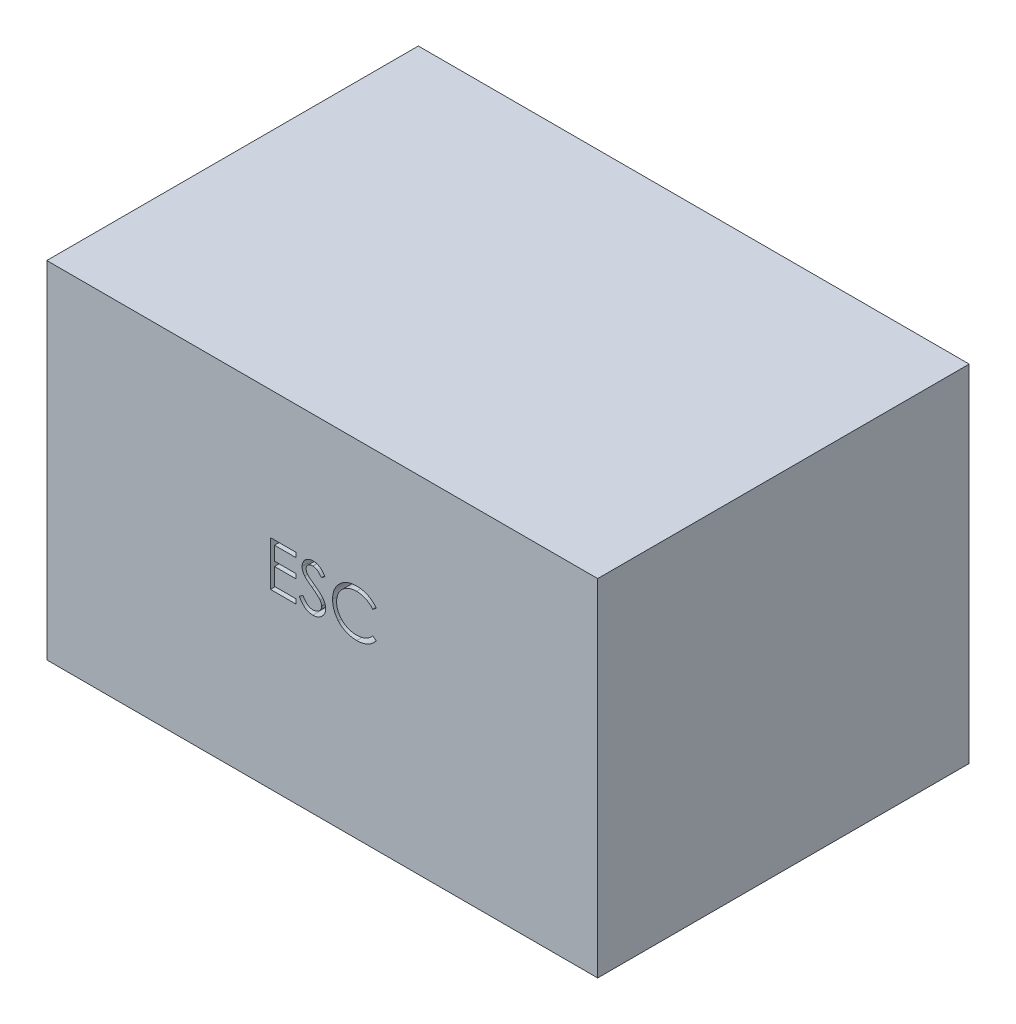
SolidWorks part; units mm, degrees
ref_plane "Front Plane" through (0, 0, 0) normal (0, 0, 1) x (1, 0, 0)
ref_plane "Top Plane" through (0, 0, 0) normal (0, 1, 0) x (1, 0, 0)
ref_plane "Right Plane" through (0, 0, 0) normal (1, 0, 0) x (0, 0, -1)
sketch "Sketch1" plane through (0, 0, 0) normal (0, 1, 0) x (1, 0, 0)
  line L1 (-21.5, -14.5) -> (21.5, -14.5)
  line L2 (-21.5, -14.5) -> (-21.5, 14.5)
  line L3 (-21.5, 14.5) -> (21.5, 14.5)
  line L4 (21.5, -14.5) -> (21.5, 14.5)
  line L5 (-21.5, -14.5) -> (21.5, 14.5) construction
  line L6 (-21.5, 14.5) -> (21.5, -14.5) construction
  point P0 (0, 0)
  dimension "D1" = 43
  dimension "D2" = 29
extrude "Boss-Extrude1" add sketch "Sketch1" along normal blind 27
sketch "Sketch2" plane through (0, 0, 14.5) normal (0, 0, 1) x (1, 0, 0)
  line L0 (-21.5, 13.5) -> (21.5, 13.5) construction
  line L1 (-21.5, 27) -> (-21.5, 0) construction
  line L2 (21.5, 27) -> (21.5, 0) construction
  text T0 "ESC"
extrude "Cut-Extrude1" cut sketch "Sketch2" against normal blind 12.7
